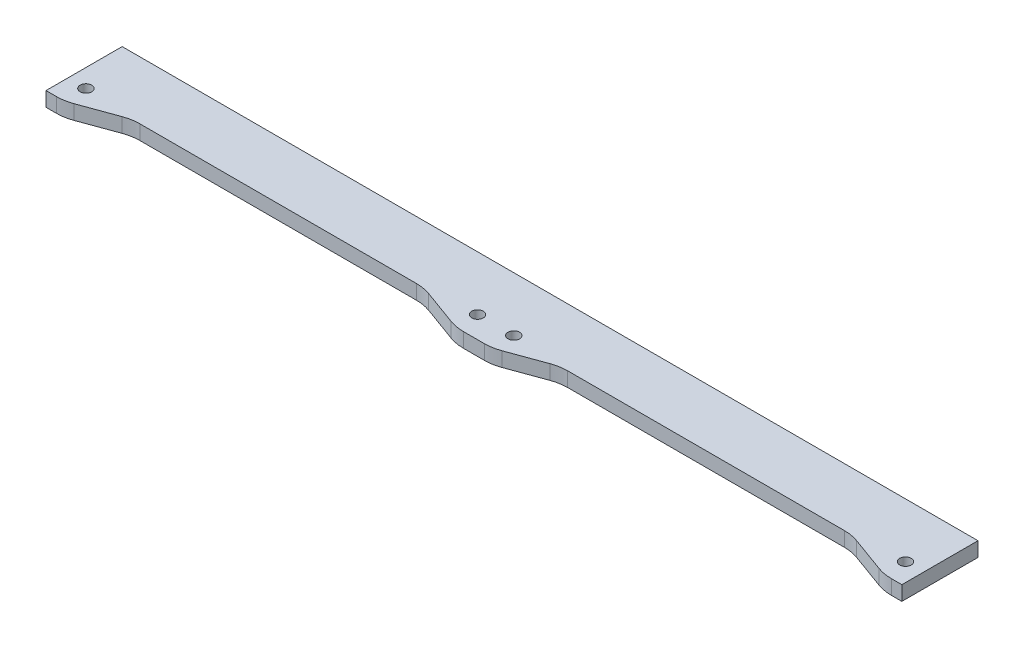
SolidWorks part; units mm, degrees
ref_plane "Front Plane" through (0, 0, 0) normal (0, 0, 1) x (1, 0, 0)
ref_plane "Top Plane" through (0, 0, 0) normal (0, 1, 0) x (1, 0, 0)
ref_plane "Right Plane" through (0, 0, 0) normal (1, 0, 0) x (0, 0, -1)
sketch "Sketch1" plane through (0, 0, 0) normal (0, 1, 0) x (1, 0, 0)
  line L0 (0, 0) -> (0, -12.5)
  line L1 (0, 0) -> (590, 0)
  line L2 (0, 0) -> (0, 35)
  line L3 (0, 35) -> (590, 35)
  line L4 (590, 0) -> (590, 35)
  line L5 (0, -12.5) -> (12.5, -12.5)
  line L6 (295, 35) -> (295, 0) construction
  line L7 (12.5, -12.5) -> (46.8435, 0)
  line L8 (307.5, -12.5) -> (282.5, -12.5)
  line L9 (282.5, -12.5) -> (248.1565, 0)
  line L10 (295, 0) -> (295, -13.5576) construction
  line L11 (307.5, -12.5) -> (341.8435, 0)
  line L12 (577.5, -12.5) -> (543.1565, 0)
  line L13 (590, -12.5) -> (577.5, -12.5)
  line L14 (590, 0) -> (590, -12.5)
  line L16 (0, 35) -> (590, 35)
  line L17 (0, 35) -> (0, 40)
  line L18 (0, 40) -> (590, 40)
  line L19 (590, 35) -> (590, 40)
  circle A1 centre (12.5, 2.5) radius 4
  circle A3 centre (577.5, 2.5) radius 4
  circle A5 centre (282.5, 2.5) radius 4
  circle A8 centre (307.5, 2.5) radius 4
  point P20 (295, -12.5)
  point P25 (295, -5)
  dimension "D3" = 8
  dimension "D4" = 8
  dimension "D5" = 12.5
  dimension "D6" = 2.5
  dimension "D8" = 12.5
  dimension "D1" = 590
  dimension "D2" = 35
  dimension "D7" = 2.5
  dimension "D9" = 15
  dimension "D10" = 0
  dimension "150" = 160
  dimension "D11" = 15
  dimension "D12" = 0
  dimension "D13" = 160
  dimension "D14" = 5
extrude "Boss-Extrude2" add sketch "Sketch1" along normal blind 10 contours L1 L4 L3 L2 A3 A1 A5 A8 | L5 L7 L1 L0 | L8 L11 L1 L9 | L14 L1 L12 L13 | L3 L19 L18 L17
fillet "Fillet1" radius 30 2 edges at (46.8435, 5, 0) (12.5, 5, 12.5)
fillet "Fillet2" radius 30 6 edges at (577.5, 5, 12.5) (543.1565, 5, 0) (341.8435, 5, 0) (307.5, 5, 12.5) (248.1565, 5, 0) (282.5, 5, 12.5)
